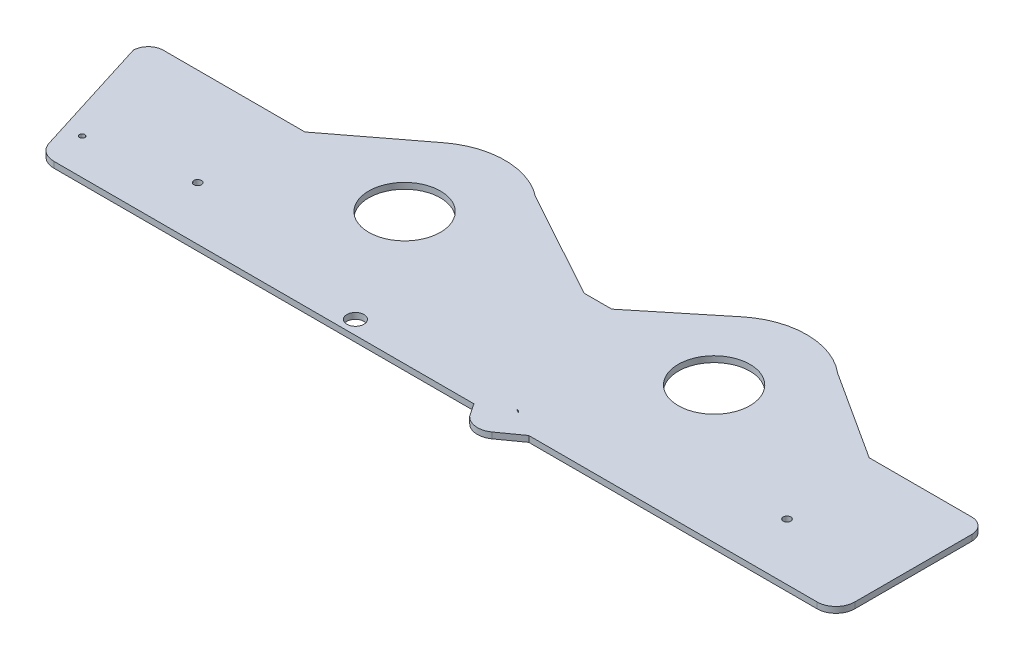
SolidWorks part; units mm, degrees
ref_plane "Front" through (0, 0, 0) normal (0, 0, 1) x (1, 0, 0)
ref_plane "Top" through (0, 0, 0) normal (0, 1, 0) x (1, 0, 0)
ref_plane "Right" through (0, 0, 0) normal (1, 0, 0) x (0, 0, -1)
sketch "Sketch1" plane through (0, 0, 0) normal (0, 1, 0) x (1, 0, 0)
  line L0 (0, 142) -> (42, 8)
  line L1 (0, 0) -> (444.5, 0)
  line L2 (0, 0) -> (0, 150)
  line L3 (0, 150) -> (444.5, 150)
  line L4 (444.5, 0) -> (444.5, 150)
  circle A0 centre (8, 142) radius 8
  circle A1 centre (50, 8) radius 8
  circle A2 centre (436.5, 142) radius 8
  circle A3 centre (436.5, 8) radius 8
  circle A5 centre (265.2813, 74.5639) radius 4.6
  circle A6 centre (172.5, 148.3404) radius 1.7
  circle A9 centre (334.1065, 150.7981) radius 2
  circle A10 centre (281.1065, 150.7981) radius 2
  circle A11 centre (122, 148.3404) radius 2
  circle A13 centre (388.4758, 100.0771) radius 2
  circle A14 centre (77.8218, 98.3272) radius 2
  circle A15 centre (182.4295, 77.3557) radius 4.5086
  circle A16 centre (334.2233, 148.8015) radius 4.0189
  circle A17 centre (25.8544, 89.0893) radius 1.4294
  dimension "D3" = 8
  dimension "D5" = 8
  dimension "D7" = 8
  dimension "D9" = 8
  dimension "D1" = 150
  dimension "D2" = 444.5
  dimension "D4" = 8
  dimension "D6" = 50
  dimension "D8" = 8
  dimension "D10" = 8
extrude "Boss-Extrude1" add sketch "Sketch1" along normal blind 3.175 contours A3 L4 A2 L3 A0 L0 A1 L1 | A1 | A0 L0 | A2 | A3
sketch "Sketch2" plane through (0, 0, 0) normal (0, 0, 1) x (1, 0, 0)
  line L1 (-78.5546, 38.0306) -> (518.9117, 38.0306)
  line L2 (-78.5546, 38.0306) -> (-78.5546, -22.9419)
  line L3 (-78.5546, -22.9419) -> (518.9117, -22.9419)
  line L4 (518.9117, 38.0306) -> (518.9117, -22.9419)
extrude "Cut-Extrude1" cut sketch "Sketch2" against normal blind 70
fillet "Fillet1" radius 10 1 edges at (22.5672, 1.5875, -70)
fillet "Fillet2" radius 10 1 edges at (444.5, 1.5875, -70)
sketch "Sketch6" plane through (0, 0, 0) normal (0, 1, 0) x (1, 0, 0)
  circle A0 centre (149, 150.0404) radius 40
  dimension "D1" = 80
  dimension "D2" = 141
extrude "Boss-Extrude2" add sketch "Sketch6" along normal blind 3.175
sketch "Sketch7" plane through (0, 0, 0) normal (0, 1, 0) x (1, 0, 0)
  line L0 (124.1645, 181.3964) -> (82.7029, 149.7505)
  line L1 (173.8355, 181.3964) -> (231.4689, 149.7505)
  line L2 (82.7029, 149.7505) -> (231.4689, 149.7505)
  line L3 (124.1645, 181.3964) -> (173.8355, 181.3964)
  arc A0 (189, 150) -> (109, 150) centre (149, 150.0404) ccw construction
extrude "Boss-Extrude3" add sketch "Sketch7" along normal blind 3.175
sketch "Sketch9" plane through (0, 0, 0) normal (0, 1, 0) x (1, 0, 0)
  line L0 (444.5, 80) -> (444.5, 142) construction
  line L1 (231.0146, 150) -> (279.2726, 150) construction
  line L2 (283.7342, 181.0103) -> (245.6734, 150)
  line L3 (245.6734, 150) -> (269, 150)
  line L4 (334.2658, 181.0103) -> (397.5744, 150)
  circle A0 centre (309, 150) radius 40
  dimension "D1" = 135.5
  dimension "D2" = 0
extrude "Boss-Extrude4" add sketch "Sketch9" along normal blind 3.175 contours A0 L2 L3 | A0
sketch "Sketch12" plane through (0, 0, 0) normal (0, 1, 0) x (1, 0, 0)
  line L0 (326.1663, 186.1292) -> (382.1065, 150)
  line L1 (349, 150) -> (436.5, 150) construction
  line L2 (382.1065, 150) -> (340.3988, 150)
  line L3 (340.3988, 150) -> (326.1663, 186.1292)
  arc A0 (349, 150) -> (283.7342, 181.0103) centre (309, 150) ccw construction
extrude "Boss-Extrude6" add sketch "Sketch12" along normal blind 3.175
sketch "Sketch13" plane through (0, 3.175, 0) normal (0, 1, 0) x (1, 0, 0)
  circle A0 centre (146, 139.8404) radius 19
  arc A1 (173.8355, 181.3964) -> (124.1645, 181.3964) centre (149, 150.0404) ccw construction
  point P5 (149, 190.0404)
  dimension "D1" = 50.2
  dimension "D3" = 38
  dimension "D2" = 138
extrude "Cut-Extrude5" cut sketch "Sketch13" against normal blind 10
sketch "Sketch14" plane through (0, 3.175, 0) normal (0, 1, 0) x (1, 0, 0)
  circle A0 centre (307.6065, 142.2981) radius 19
  arc A2 (334.871, 180.5072) -> (283.7342, 181.0103) centre (309, 150) ccw construction
  point P6 (309.3935, 189.9981)
  dimension "D1" = 74.5
  dimension "D3" = 38
  dimension "D2" = 47.7
extrude "Cut-Extrude6" cut sketch "Sketch14" against normal blind 10
sketch "Sketch15" plane through (0, 3.175, 0) normal (0, 1, 0) x (1, 0, 0)
  line L0 (444.5, 80) -> (444.5, 142) construction
  line L2 (231.0146, 150) -> (245.6734, 150) construction
  line L3 (281.6714, 70) -> (270.3236, 61.8707)
  line L4 (29.9125, 70) -> (264.7058, 70) construction
  line L5 (264.5, 80) -> (251.9232, 70.9902)
  line L6 (264.5, 80) -> (281.6714, 70)
  line L7 (251.9232, 70.9902) -> (257.164, 63.2042)
  circle A0 centre (264.5, 70) radius 10
  dimension "D1" = 180
  dimension "D3" = 20
  dimension "D2" = 80
extrude "Boss-Extrude7" add sketch "Sketch15" along normal blind 10 and the other way blind 3.175
sketch "Sketch16" plane through (0, 13.175, 0) normal (0, 1, 0) x (1, 0, 0)
  line L1 (247.445, 85.003) -> (286.8256, 85.003)
  line L2 (247.445, 85.003) -> (247.445, 51.0981)
  line L3 (247.445, 51.0981) -> (286.8256, 51.0981)
  line L4 (286.8256, 85.003) -> (286.8256, 51.0981)
extrude "Cut-Extrude7" cut sketch "Sketch16" against normal blind 10
